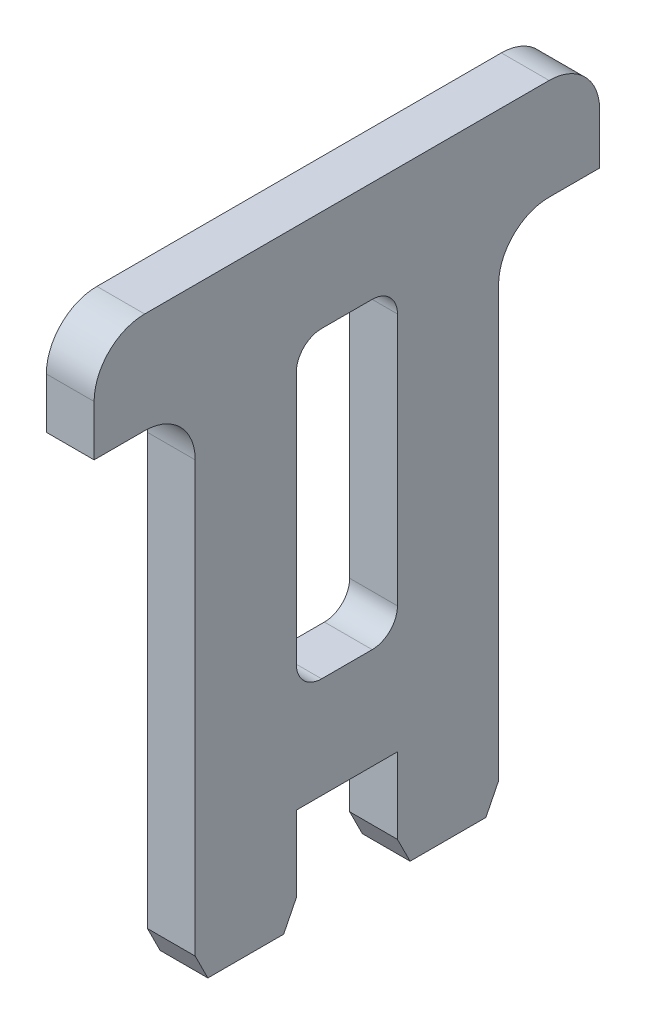
SolidWorks part; units mm, degrees
ref_plane "Front Plane" through (0, 0, 0) normal (0, 0, 1) x (1, 0, 0)
ref_plane "Top Plane" through (0, 0, 0) normal (0, 1, 0) x (1, 0, 0)
ref_plane "Right Plane" through (0, 0, 0) normal (1, 0, 0) x (0, 0, -1)
sketch "Sketch1" plane through (0, 0, 0) normal (1, 0, 0) x (0, 0, -1)
  line L0 (6.35, -25.4) -> (19.05, -25.4) construction
  line L1 (-6.35, -25.4) -> (6.35, -25.4)
  line L2 (-19.05, -25.4) -> (-19.05, 25.4)
  line L3 (-19.05, 25.4) -> (19.05, 25.4) construction
  line L4 (19.05, -25.4) -> (19.05, 25.4)
  line L5 (-19.05, -25.4) -> (19.05, 25.4) construction
  line L6 (-19.05, 25.4) -> (19.05, -25.4) construction
  line L7 (-6.35, -38.1) -> (-19.05, -38.1)
  line L8 (-6.35, -38.1) -> (-6.35, -25.4)
  line L9 (-6.35, -25.4) -> (-19.05, -25.4) construction
  line L10 (-19.05, -38.1) -> (-19.05, -25.4)
  line L11 (-6.35, -38.1) -> (-19.05, -25.4) construction
  line L12 (-6.35, -25.4) -> (-19.05, -38.1) construction
  line L13 (6.35, -38.1) -> (19.05, -38.1)
  line L14 (6.35, -38.1) -> (6.35, -25.4)
  line L15 (6.35, -25.4) -> (19.05, -25.4) construction
  line L16 (19.05, -38.1) -> (19.05, -25.4)
  line L17 (6.35, -38.1) -> (19.05, -25.4) construction
  line L18 (6.35, -25.4) -> (19.05, -38.1) construction
  line L19 (-19.05, -25.4) -> (-6.35, -25.4) construction
  line L20 (19.05, 25.4) -> (-19.05, 25.4) construction
  line L21 (31.75, 38.1) -> (-31.75, 38.1)
  line L22 (31.75, 38.1) -> (31.75, 25.4)
  line L23 (31.75, 25.4) -> (19.05, 25.4)
  line L24 (-31.75, 38.1) -> (-31.75, 25.4)
  line L25 (31.75, 38.1) -> (-31.75, 25.4) construction
  line L26 (31.75, 25.4) -> (-31.75, 38.1) construction
  line L27 (-19.05, 25.4) -> (-31.75, 25.4)
  point P0 (0, 0)
  point P6 (-12.7, -31.75)
  point P7 (12.7, -31.75)
  point P11 (0, 31.75)
  dimension "D1" = 50.8
  dimension "D2" = 12.7
  dimension "D3" = 25.4
  dimension "D4" = 12.7
  dimension "D5" = 12.7
  dimension "D6" = 12.7
extrude "Boss-Extrude1" add sketch "Sketch1" along normal mid plane 6
fillet "Fillet1" radius 6.35 4 edges at (0, 25.4, 19.05) (0, 25.4, -19.05) (0, 38.1, 31.75) (0, 38.1, -31.75)
sketch "Sketch2" plane through (3, 0, 0) normal (1, 0, 0) x (0, 0, -1)
  line L0 (25.4, 38.1) -> (-25.4, 38.1) construction
  line L1 (-6.35, -12.7) -> (6.35, -12.7)
  line L2 (-6.35, -12.7) -> (-6.35, 25.4)
  line L3 (-6.35, 25.4) -> (6.35, 25.4)
  line L4 (6.35, -12.7) -> (6.35, 25.4)
  line L5 (-6.35, -12.7) -> (6.35, 25.4) construction
  line L6 (-6.35, 25.4) -> (6.35, -12.7) construction
  line L7 (-6.35, -25.4) -> (6.35, -25.4) construction
  point P0 (0, 6.35)
  point P6 (0, 0)
  point P7 (6.3311, 26.9526)
  point P12 (0, 0)
  dimension "D1" = 12.7
  dimension "D2" = 12.7
  dimension "D3" = 12.7
extrude "Cut-Extrude1" cut sketch "Sketch2" against normal through all both and the other way through all
fillet "Fillet2" radius 3.175 4 edges at (0, -12.7, 6.35) (0, -12.7, -6.35) (0, 25.4, -6.35) (0, 25.4, 6.35)
chamfer "Chamfer1" distance 3.175 distance2 1.5875 2 edges at (0, -38.1, -6.35) (0, -38.1, 19.05)
chamfer "Chamfer2" distance 1.5875 distance2 3.175 2 edges at (0, -38.1, -19.05) (0, -38.1, 6.35)
equation "\"D1@Boss-Extrude1\"=6mm"
